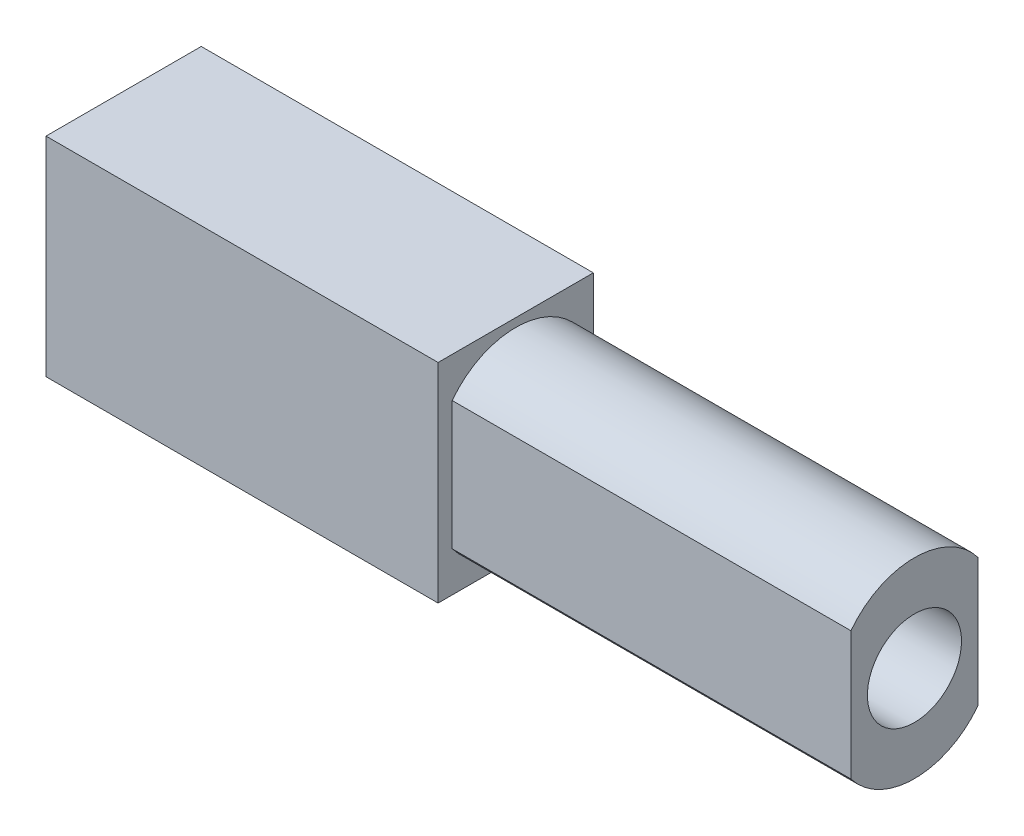
SolidWorks part; units mm, degrees
ref_plane "Front Plane" through (0, 0, 0) normal (0, 0, 1) x (1, 0, 0)
ref_plane "Top Plane" through (0, 0, 0) normal (0, 1, 0) x (1, 0, 0)
ref_plane "Right Plane" through (0, 0, 0) normal (1, 0, 0) x (0, 0, -1)
sketch "Sketch1" plane through (0, 0, 0) normal (1, 0, 0) x (0, 0, -1)
  line L0 (-6.0706, 6.1341) -> (6.0706, -6.1341) construction
  line L4 (-6.0706, 6.1341) -> (-6.0706, -6.1341)
  line L5 (6.0706, 6.1341) -> (6.0706, -6.1341)
  line L6 (-6.0706, -6.1341) -> (6.0706, 6.1341) construction
  arc A2 (-6.0706, 6.1341) -> (6.0706, 6.1341) centre (0, 1.5284) cw
  arc A3 (-6.0706, -6.1341) -> (6.0706, -6.1341) centre (0, -1.5284) ccw
  point P0 (0, 0)
  point P10 (0, 0)
  point P11 (0, 0)
  dimension "D3" = 7.62
  dimension "D4" = 6.0706
  dimension "D1" = 12.1412
  dimension "D2" = 12.2682
extrude "Boss-Extrude1" add sketch "Sketch1" along normal blind 38.1 contours A2 L5 A3 L4
sketch "Sketch2" plane through (38.1, 0, 0) normal (1, 0, 0) x (0, 0, -1)
  circle A0 centre (0, 0) radius 4.4958
  dimension "D1" = 8.9916
extrude "Cut-Extrude1" cut sketch "Sketch2" against normal blind 25.4
sketch "Sketch4" plane through (0, 0, 0) normal (-1, 0, 0) x (0, 0, 1)
  line L3 (-7.4168, -9.9568) -> (7.4168, -9.9568)
  line L6 (-7.4168, -9.9568) -> (-7.4168, 9.9568)
  line L7 (-7.4168, 9.9568) -> (7.4168, 9.9568)
  line L8 (7.4168, -9.9568) -> (7.4168, 9.9568)
  line L9 (-7.4168, -9.9568) -> (7.4168, 9.9568) construction
  line L10 (-7.4168, 9.9568) -> (7.4168, -9.9568) construction
  point P0 (0, 0)
  dimension "D1" = 14.8336
  dimension "D2" = 19.9136
extrude "Boss-Extrude2" add sketch "Sketch4" along normal blind 37.465
